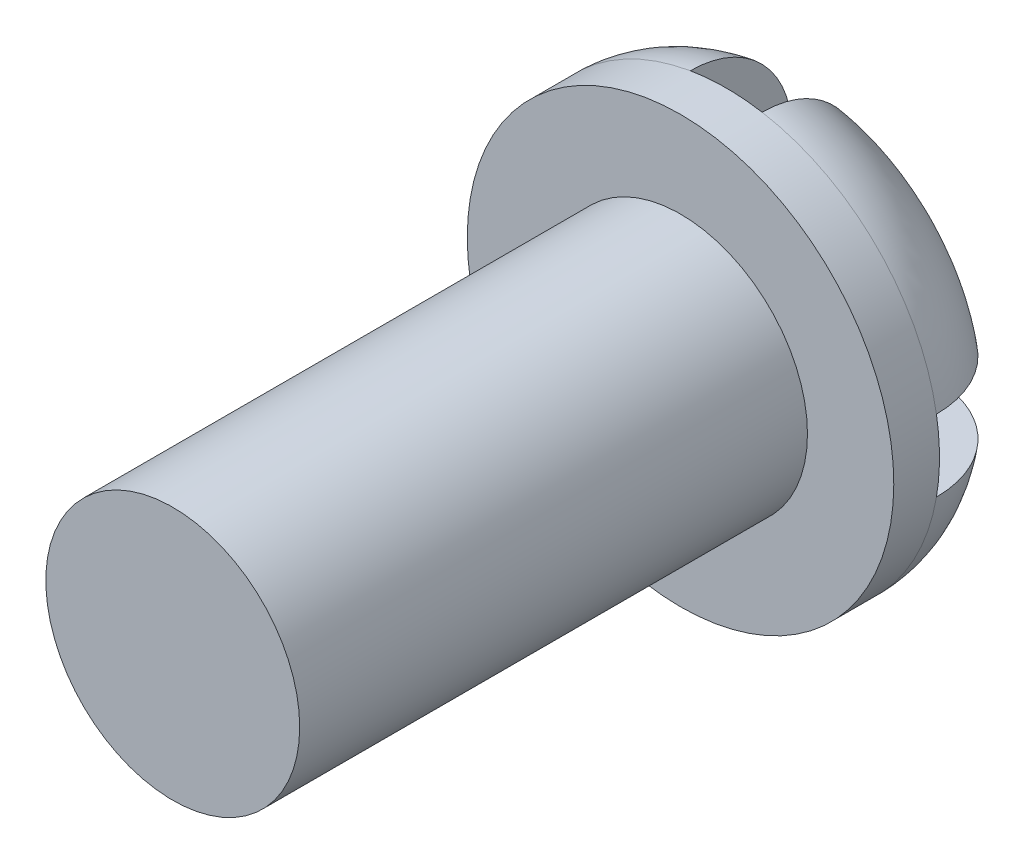
SolidWorks part; units mm, degrees
ref_plane "前视基准面" through (0, 0, 0) normal (0, 0, 1) x (1, 0, 0)
ref_plane "上视基准面" through (0, 0, 0) normal (0, 1, 0) x (1, 0, 0)
ref_plane "右视基准面" through (0, 0, 0) normal (1, 0, 0) x (0, 0, -1)
sketch "草图1" plane through (0, 0, 0) normal (0, 0, 1) x (1, 0, 0)
  circle A0 centre (0, 0) radius 2.5
  dimension "D1" = 5
extrude "凸台-拉伸1" add sketch "草图1" along normal blind 10
sketch "草图2" plane through (0, 0, 0) normal (0, 0, -1) x (-1, 0, 0)
  circle A0 centre (0, 0) radius 4.2
  dimension "D1" = 8.4
extrude "凸台-拉伸2" add sketch "草图2" along normal blind 2.9
fillet "圆角1" radius 2 1 edges at (-4.2, 0, -2.9)
sketch "草图3" plane through (0, 0, -2.9) normal (0, 0, -1) x (-1, 0, 0)
  line L0 (-0.7071, 0.7071) -> (-0.7071, 6.0064)
  line L1 (1, -1) -> (-1, -1) construction
  line L2 (1, -1) -> (1, 1) construction
  line L3 (1, 1) -> (-1, 1) construction
  line L4 (-1, -1) -> (-1, 1) construction
  line L5 (1, -1) -> (-1, 1) construction
  line L6 (1, 1) -> (-1, -1) construction
  line L7 (0.7071, 0.7071) -> (0.7071, 6.0064)
  line L8 (0.7071, 6.0064) -> (-0.7071, 6.0064)
  line L9 (0.7071, 0.7071) -> (6.0064, 0.7071)
  line L10 (0.7071, -0.7071) -> (6.0064, -0.7071)
  line L11 (6.0064, -0.7071) -> (6.0064, 0.7071)
  line L12 (0.7071, -0.7071) -> (0.7071, -6.0064)
  line L13 (-0.7071, -0.7071) -> (-0.7071, -6.0064)
  line L14 (-0.7071, -6.0064) -> (0.7071, -6.0064)
  line L15 (-0.7071, -0.7071) -> (-6.0064, -0.7071)
  line L16 (-0.7071, 0.7071) -> (-6.0064, 0.7071)
  line L17 (-6.0064, 0.7071) -> (-6.0064, -0.7071)
  circle A0 centre (0, 0) radius 1 construction
  dimension "D1" = 4
extrude "切除-拉伸1" cut sketch "草图3" against normal blind 2
